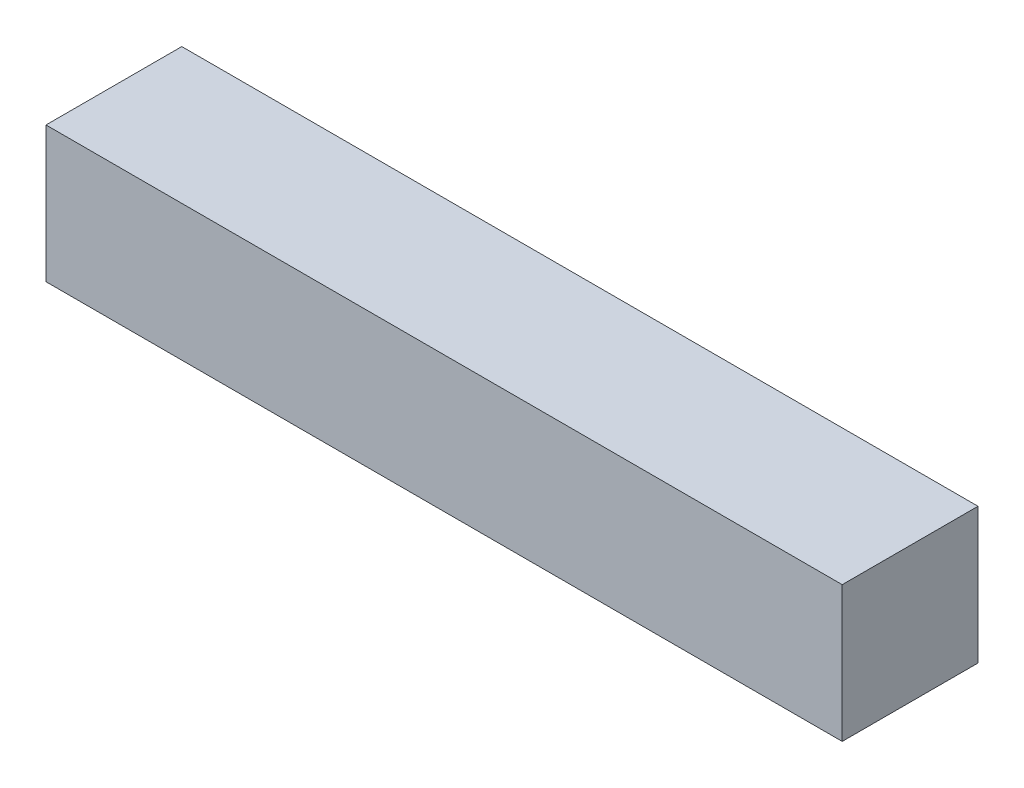
SolidWorks part; units mm, degrees
ref_plane "Front Plane" through (0, 0, 0) normal (0, 0, 1) x (1, 0, 0)
ref_plane "Top Plane" through (0, 0, 0) normal (0, 1, 0) x (1, 0, 0)
ref_plane "Right Plane" through (0, 0, 0) normal (1, 0, 0) x (0, 0, -1)
sketch "Sketch1" plane through (0, 0, 0) normal (1, 0, 0) x (0, 0, -1)
  line L1 (-33, -33) -> (33, -33)
  line L2 (-33, -33) -> (-33, 33)
  line L3 (-33, 33) -> (33, 33)
  line L4 (33, -33) -> (33, 33)
  line L5 (-33, -33) -> (33, 33) construction
  line L6 (-33, 33) -> (33, -33) construction
  point P0 (0, 0)
  dimension "D1" = 66
  dimension "D2" = 66
extrude "Boss-Extrude1" add sketch "Sketch1" along normal blind 387
